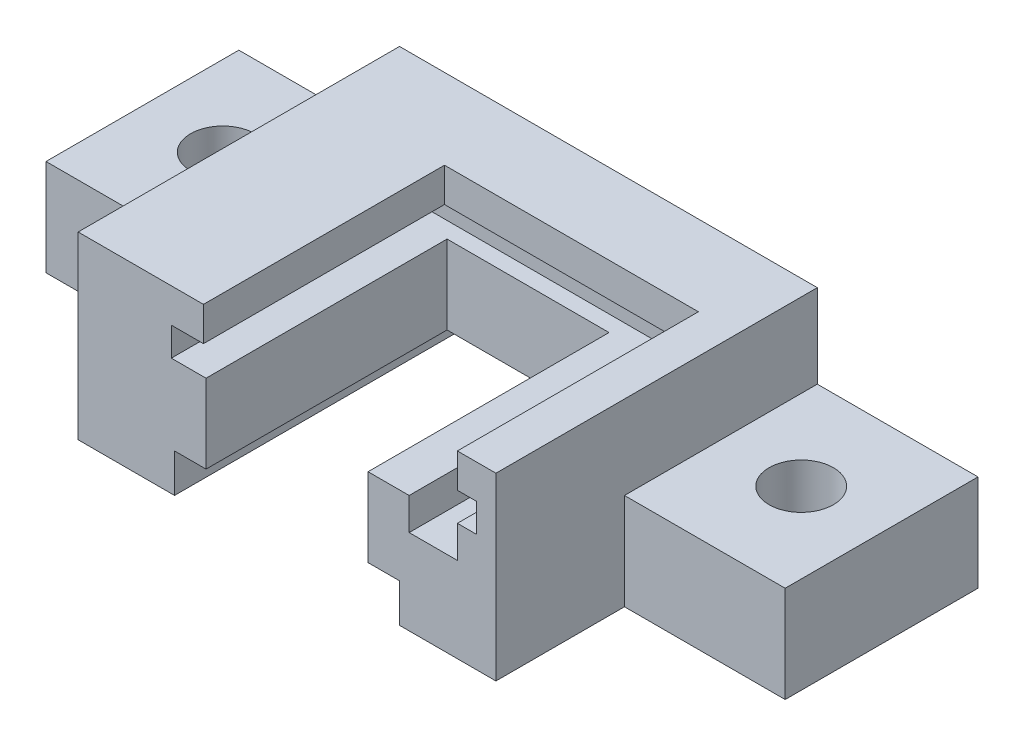
SolidWorks part; units mm, degrees
ref_plane "Front Plane" through (0, 0, 0) normal (0, 0, 1) x (1, 0, 0)
ref_plane "Top Plane" through (0, 0, 0) normal (0, 1, 0) x (1, 0, 0)
ref_plane "Right Plane" through (0, 0, 0) normal (1, 0, 0) x (0, 0, -1)
sketch "Sketch2" plane through (0, 0, 0) normal (0, 0, 1) x (1, 0, 0)
  line L0 (13, 0) -> (9.6353, 0) construction
  line L1 (-13, 5.6) -> (13, 5.6)
  line L2 (-13, 5.6) -> (-13, -5.6)
  line L3 (-13, -5.6) -> (13, -5.6)
  line L4 (13, 5.6) -> (13, -5.6)
  line L5 (0, -5.6) -> (0, -3.1467) construction
  dimension "D1" = 26
  dimension "D2" = 11.2
  dimension "D3" = 0
  dimension "D4" = 0
extrude "Boss-Extrude1" add sketch "Sketch2" along normal blind 20
sketch "Sketch6" plane through (0, 0, 20) normal (0, 0, 1) x (1, 0, 0)
  line L0 (-13, -5.6) -> (13, -5.6) construction
  line L1 (-7, -3.2) -> (7, -3.2)
  line L2 (-7, -3.2) -> (-7, -5.6)
  line L3 (-7, -5.6) -> (7, -5.6)
  line L4 (7, -3.2) -> (7, -5.6)
  line L5 (0, -5.6) -> (0, -4.6516) construction
  line L6 (0, -5.6) -> (0, -4.6516) construction
  dimension "D1" = 14
  dimension "D2" = 2.4
  dimension "D3" = 0
  dimension "D4" = 0
sketch "Sketch7" plane through (0, 0, 20) normal (0, 0, 1) x (1, 0, 0)
  line L0 (0, -3.2) -> (0, -2.2535) construction
  line L1 (-5.04, 1.7) -> (5.04, 1.7)
  line L2 (-5.04, 1.7) -> (-5.04, -3.2)
  line L3 (-5.04, -3.2) -> (5.04, -3.2)
  line L4 (5.04, 1.7) -> (5.04, -3.2)
  line L5 (-7, -3.2) -> (7, -3.2) construction
  dimension "D1" = 4.9
  dimension "D2" = 10.08
  dimension "D3" = 0
  dimension "D4" = 0
sketch "Sketch8" plane through (0, 0, 20) normal (0, 0, 1) x (1, 0, 0)
  line L0 (-5.04, 1.7) -> (5.04, 1.7) construction
  line L1 (-7.2, 3.48) -> (11.8, 3.48)
  line L2 (-7.2, 3.48) -> (-7.2, 1.7)
  line L3 (-7.2, 1.7) -> (11.8, 1.7)
  line L4 (11.8, 3.48) -> (11.8, 1.7)
  dimension "D1" = 19
  dimension "D2" = 1.78
  dimension "D3" = 7.2
  dimension "D4" = 0
sketch "Sketch9" plane through (0, 0, 20) normal (0, 0, 1) x (1, 0, 0)
  line L0 (-7.2, 3.48) -> (-7.2, 1.7) construction
  line L1 (-5.2, 5.6) -> (10.6, 5.6)
  line L2 (-5.2, 5.6) -> (-5.2, 3.48)
  line L3 (-5.2, 3.48) -> (10.6, 3.48)
  line L4 (10.6, 5.6) -> (10.6, 3.48)
  line L5 (11.8, 3.48) -> (11.8, 1.7) construction
  line L6 (-7.2, 3.48) -> (11.8, 3.48) construction
  line L7 (13, 5.6) -> (-13, 5.6) construction
  dimension "D1" = 2
  dimension "D2" = 1.2
  dimension "D3" = 0
  dimension "D4" = 0
sketch "Sketch10" plane through (0, 0, 20) normal (0, 0, 1) x (1, 0, 0)
  line L0 (11.8, 3.48) -> (11.8, 1.7) construction
  line L1 (7.6, 1.7) -> (10.6, 1.7)
  line L2 (7.6, 1.7) -> (7.6, -0.3)
  line L3 (7.6, -0.3) -> (10.6, -0.3)
  line L4 (10.6, 1.7) -> (10.6, -0.3)
  line L5 (-7.2, 1.7) -> (11.8, 1.7) construction
  dimension "D1" = 2
  dimension "D2" = 3
  dimension "D3" = 1.2
  dimension "D4" = 0
extrude "Cut-Extrude1" cut sketch "Sketch6" against normal blind 20
extrude "Cut-Extrude2" cut sketch "Sketch7" against normal blind 15
extrude "Cut-Extrude3" cut sketch "Sketch8" against normal blind 16
extrude "Cut-Extrude4" cut sketch "Sketch9" against normal blind 15
extrude "Cut-Extrude5" cut sketch "Sketch10" against normal blind 15
sketch "Sketch11" plane through (0, -5.6, 0) normal (0, -1, 0) x (1, 0, 0)
  line L0 (-13, 10) -> (-11.5021, 10) construction
  line L1 (-13, 20) -> (-13, 0) construction
  line L2 (-13, 0) -> (-7, 0) construction
  line L3 (-10, 0) -> (-10, 1.1276) construction
  line L4 (-11.55, 5) -> (-8.45, 5)
  arc A0 (-11.55, 5) -> (-8.45, 5) centre (-10, 5) cw
  dimension "D1" = 3.1
  dimension "D2" = 0
  dimension "D3" = 5
sketch "Sketch12" plane through (0, -5.6, 0) normal (0, -1, 0) x (1, 0, 0)
  line L0 (-11.5, 15) -> (-8.5, 15)
  line L1 (-10, 15) -> (-10, 15.7701) construction
  arc A0 (-11.5, 15) -> (-8.5, 15) centre (-10, 15) ccw
  dimension "D1" = 3
  dimension "D2" = 0
  dimension "D3" = 5
sketch "Sketch13" plane through (0, -5.6, 0) normal (0, -1, 0) x (1, 0, 0)
  line L0 (7, 0) -> (13, 0) construction
  line L1 (10, 0) -> (10, 1.2586) construction
  line L2 (13, 20) -> (13, 0) construction
  line L3 (13, 10) -> (11.9152, 10) construction
  line L4 (8.5, 5) -> (11.5, 5)
  line L5 (10, 5) -> (10, 6.238) construction
  arc A0 (8.5, 5) -> (11.5, 5) centre (10, 5) cw
  dimension "D1" = 3
  dimension "D2" = 1.5
  dimension "D3" = 5
sketch "Sketch14" plane through (0, -5.6, 0) normal (0, -1, 0) x (1, 0, 0)
  line L0 (8.45, 15) -> (11.55, 15)
  line L1 (13, 10) -> (11.9152, 10) construction
  line L2 (10, 15) -> (10, 16.0943) construction
  arc A0 (8.45, 15) -> (11.55, 15) centre (10, 15) ccw
  dimension "D1" = 3.1
  dimension "D2" = 5
  dimension "D3" = 0
revolve "Cut-Revolve3" cut sketch "Sketch11" angle 180 about L4
revolve "Revolve2" add sketch "Sketch12" angle 360 about L0
revolve "Cut-Revolve4" cut sketch "Sketch14" angle 360 about L0
revolve "Revolve3" add sketch "Sketch13" angle 360 about L4
sketch "Sketch15" plane through (-13, 0, 0) normal (-1, 0, 0) x (0, 0, 1)
  line L0 (0, 5.6) -> (0, -5.6) construction
  line L1 (12, 0.4) -> (0, 0.4)
  line L2 (12, 0.4) -> (12, -5.6)
  line L3 (12, -5.6) -> (0, -5.6)
  line L4 (0, 0.4) -> (0, -5.6)
  line L5 (20, -5.6) -> (0, -5.6) construction
  dimension "D1" = 0
  dimension "D2" = 0
  dimension "D3" = 6
  dimension "D4" = 12
extrude "Boss-Extrude2" add sketch "Sketch15" along normal blind 10
sketch "Sketch16" plane through (13, 0, 0) normal (1, 0, 0) x (0, 0, -1)
  line L0 (-20, -5.6) -> (0, -5.6) construction
  line L1 (-12, -5.6) -> (0, -5.6)
  line L2 (-12, -5.6) -> (-12, 0.4)
  line L3 (-12, 0.4) -> (0, 0.4)
  line L4 (0, -5.6) -> (0, 0.4)
  line L5 (0, -5.6) -> (0, 5.6) construction
  dimension "D1" = 0
  dimension "D2" = 0
  dimension "D3" = 6
  dimension "D4" = 12
extrude "Boss-Extrude3" add sketch "Sketch16" along normal blind 10
sketch "Sketch17" plane through (0, -5.6, 0) normal (0, -1, 0) x (1, 0, 0)
  line L0 (-23, 12) -> (-13, 12) construction
  line L1 (-18, 12) -> (-18, 10.8517) construction
  line L2 (-23, 0) -> (-23, 12) construction
  line L3 (-23, 6) -> (-21.8135, 6) construction
  circle A0 centre (-18, 6) radius 2
  dimension "D1" = 4
  dimension "D2" = 0
  dimension "D3" = 0
sketch "Sketch18" plane through (0, -5.6, 0) normal (0, -1, 0) x (1, 0, 0)
  line L0 (23, 12) -> (13, 12) construction
  line L1 (18, 12) -> (18, 10.2463) construction
  line L2 (23, 12) -> (23, 0) construction
  line L3 (23, 6) -> (21.7422, 6) construction
  circle A0 centre (18, 6) radius 2
  dimension "D1" = 4
  dimension "D2" = 0
  dimension "D3" = 0
extrude "Cut-Extrude6" cut sketch "Sketch17" against normal blind 12
extrude "Cut-Extrude7" cut sketch "Sketch18" against normal blind 12 contours A0
